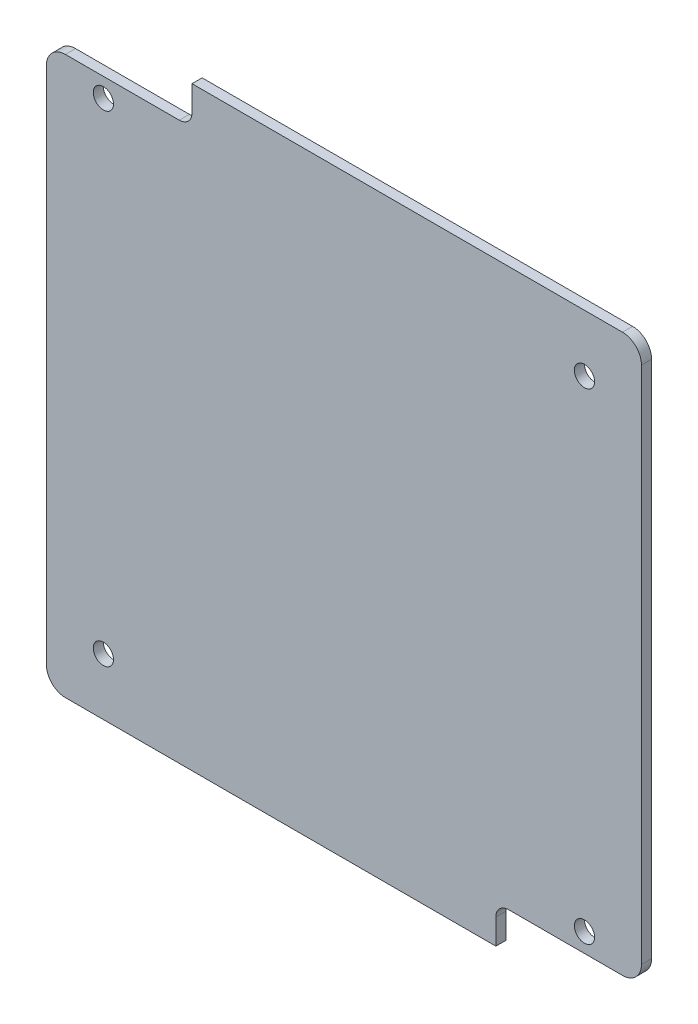
SolidWorks part; units mm, degrees
ref_plane "Front Plane" through (0, 0, 0) normal (0, 0, 1) x (1, 0, 0)
ref_plane "Top Plane" through (0, 0, 0) normal (0, 1, 0) x (1, 0, 0)
ref_plane "Right Plane" through (0, 0, 0) normal (1, 0, 0) x (0, 0, -1)
sketch "Sketch1" plane through (0, 0, 0) normal (0, 0, 1) x (1, 0, 0)
  line L1 (-16.5653, -2.0481) -> (-84.5653, -2.0481)
  line L2 (-87.5653, 0.9519) -> (-87.5653, 82.9519)
  line L3 (-64.5653, 91.9519) -> (3.4347, 91.9519)
  line L4 (6.4347, 88.9519) -> (6.4347, 6.9519)
  line L5 (-14.5653, 3.9519) -> (3.4347, 3.9519)
  line L20 (-64.5653, 91.9519) -> (-64.5653, 87.9519)
  line L22 (-66.5653, 85.9519) -> (-84.5653, 85.9519)
  line L26 (-16.5653, 1.9519) -> (-16.5653, -2.0481)
  arc A0 (3.4347, 3.9519) -> (6.4347, 6.9519) centre (3.4347, 6.9519) ccw
  arc A1 (-14.5653, 3.9519) -> (-16.5653, 1.9519) centre (-14.5653, 1.9519) ccw
  arc A2 (-87.5653, 0.9519) -> (-84.5653, -2.0481) centre (-84.5653, 0.9519) ccw
  arc A3 (3.4347, 91.9519) -> (6.4347, 88.9519) centre (3.4347, 88.9519) cw
  arc A4 (-64.5653, 87.9519) -> (-66.5653, 85.9519) centre (-66.5653, 87.9519) cw
  arc A5 (-84.5653, 85.9519) -> (-87.5653, 82.9519) centre (-84.5653, 82.9519) ccw
  dimension "D5" = 3
  dimension "D7" = 6
  dimension "D6" = 3
  dimension "D9" = 2
  dimension "D10" = 3
  dimension "D13" = 2
  dimension "D14" = 3
  dimension "D2" = 94
  dimension "D3" = 94
  dimension "D4" = 6
  dimension "D11" = 23
extrude "Boss-Extrude1" add sketch "Sketch1" along normal blind 1.6
hole_wizard "Ø3.2 (3.2) Diameter Hole3" positions "Sketch7" profile "Sketch6" hole size "Ø3.2" standard "Ansi Metric" end condition up to next
sketch "Sketch7" plane through (0, 0, 0) normal (0, 0, -1) x (-1, 0, 0)
  line L1 (87.5653, 82.9519) -> (87.5653, 0.9519) construction
  line L2 (-3.4347, 91.9519) -> (64.5653, 91.9519) construction
  line L3 (84.5653, -2.0481) -> (16.5653, -2.0481) construction
  line L4 (-6.4347, 6.9519) -> (-6.4347, 88.9519) construction
  point P6 (78.5653, 6.9519)
  point P9 (78.5653, 82.9519)
  point P12 (2.5653, 82.9519)
  point P15 (2.5653, 6.9519)
  dimension "D1" = 9
  dimension "D2" = 9
  dimension "D3" = 9
  dimension "D4" = 9
  dimension "D5" = 9
  dimension "D6" = 9
  dimension "D7" = 9
  dimension "D8" = 9
sketch "Sketch6" plane through (-78.5653, 6.9519, 0) normal (1, 0, 0) x (0, 1, 0)
  line L0 (0, 0) -> (0, 1.6)
  line L1 (0, 1.6) -> (1.6, 1.6)
  line L2 (1.6, 1.6) -> (1.6, 0)
  line L5 (1.6, 0) -> (0, 0)
  line L11 (0, -6.35) -> (0, 107.95) construction
  dimension "Thru Hole Dia." = 3.2
  dimension "Thru Hole Depth" = 1.6
